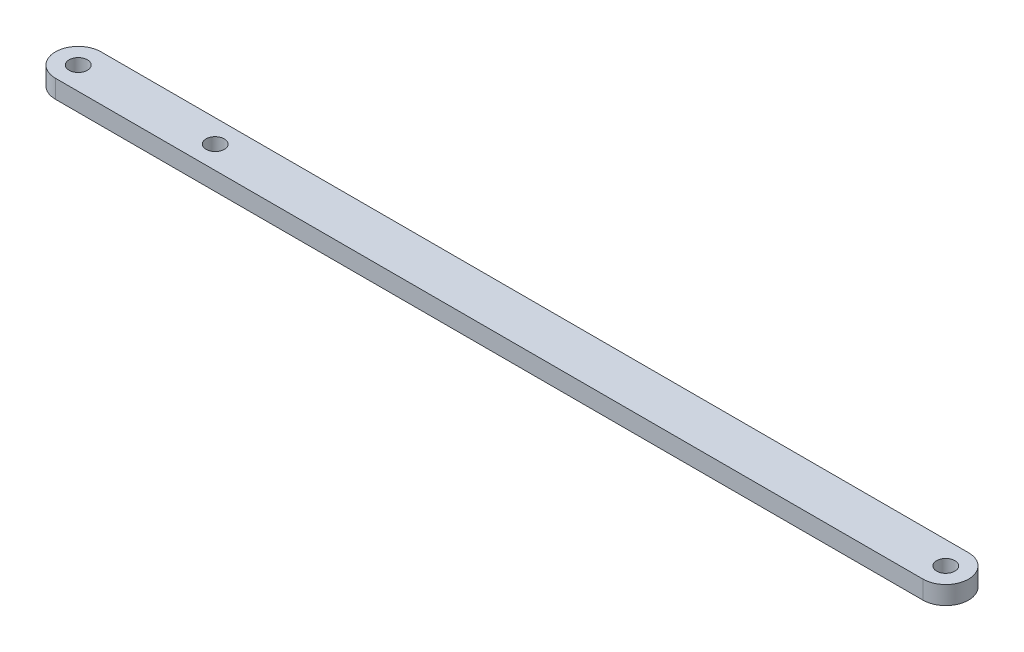
SolidWorks part; units mm, degrees
ref_plane "Front Plane" through (0, 0, 0) normal (0, 0, 1) x (1, 0, 0)
ref_plane "Top Plane" through (0, 0, 0) normal (0, 1, 0) x (1, 0, 0)
ref_plane "Right Plane" through (0, 0, 0) normal (1, 0, 0) x (0, 0, -1)
sketch "Sketch1" plane through (0, 0, 0) normal (0, 1, 0) x (1, 0, 0)
  line L0 (-10, 0) -> (85, 0) construction
  line L1 (-10, 2.5) -> (85, 2.5)
  line L2 (-10, -2.5) -> (85, -2.5)
  arc A0 (-10, 2.5) -> (-10, -2.5) centre (-10, 0) ccw
  arc A1 (85, -2.5) -> (85, 2.5) centre (85, 0) ccw
  circle A2 centre (85, 0) radius 1
  circle A3 centre (-10, 0) radius 1
  circle A4 centre (5, 0) radius 1
  point P3 (37.5, 0)
  dimension "D3" = 2
  dimension "D4" = 2.5
  dimension "D5" = 2
  dimension "D6" = 2
  dimension "D1" = 95
  dimension "D2" = 15
  dimension "D12" = 10
extrude "Boss-Extrude1" add sketch "Sketch1" along normal blind 2
